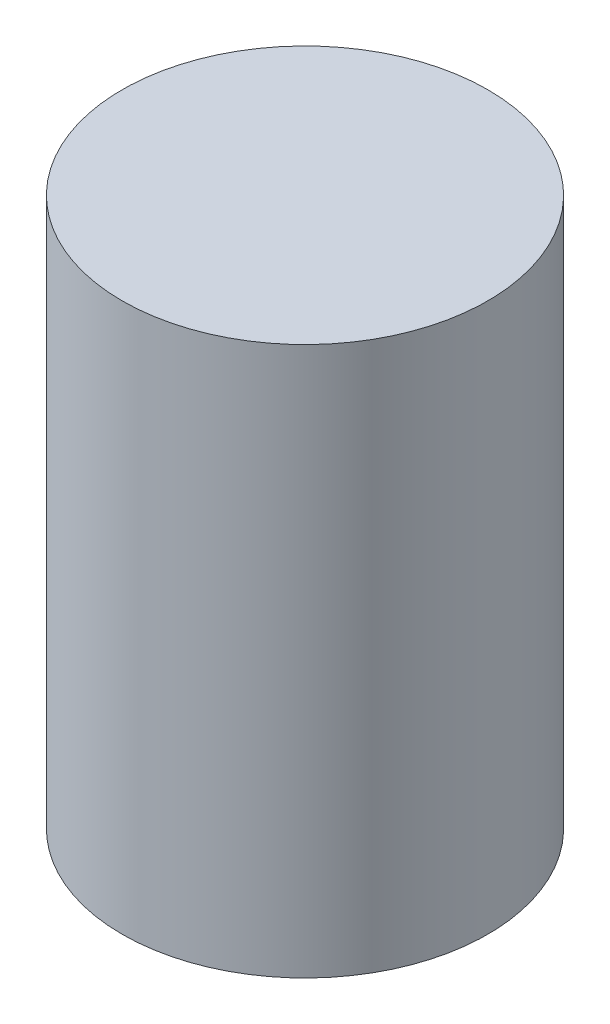
SolidWorks part; units mm, degrees
ref_plane "Front Plane" through (0, 0, 0) normal (0, 0, 1) x (1, 0, 0)
ref_plane "Top Plane" through (0, 0, 0) normal (0, 1, 0) x (1, 0, 0)
ref_plane "Right Plane" through (0, 0, 0) normal (1, 0, 0) x (0, 0, -1)
sketch "Sketch1" plane through (0, 0, 0) normal (0, 1, 0) x (1, 0, 0)
  circle A0 centre (0, 0) radius 3.175
  dimension "D1" = 6.35
extrude "Boss-Extrude1" add sketch "Sketch1" along normal blind 9.525
equation "\"R\"= 1.5in'radius of rotor"
equation "\"E\"= .125in'eccentricity"
equation "\"R_r\"= .125in'radius of roller"
equation "\"N\"= 14'number of rollers"
equation "\"R_o\"= .2in'output disk pin diameter"
equation "\"D1@Sketch1\"=2*\"R_r\""
